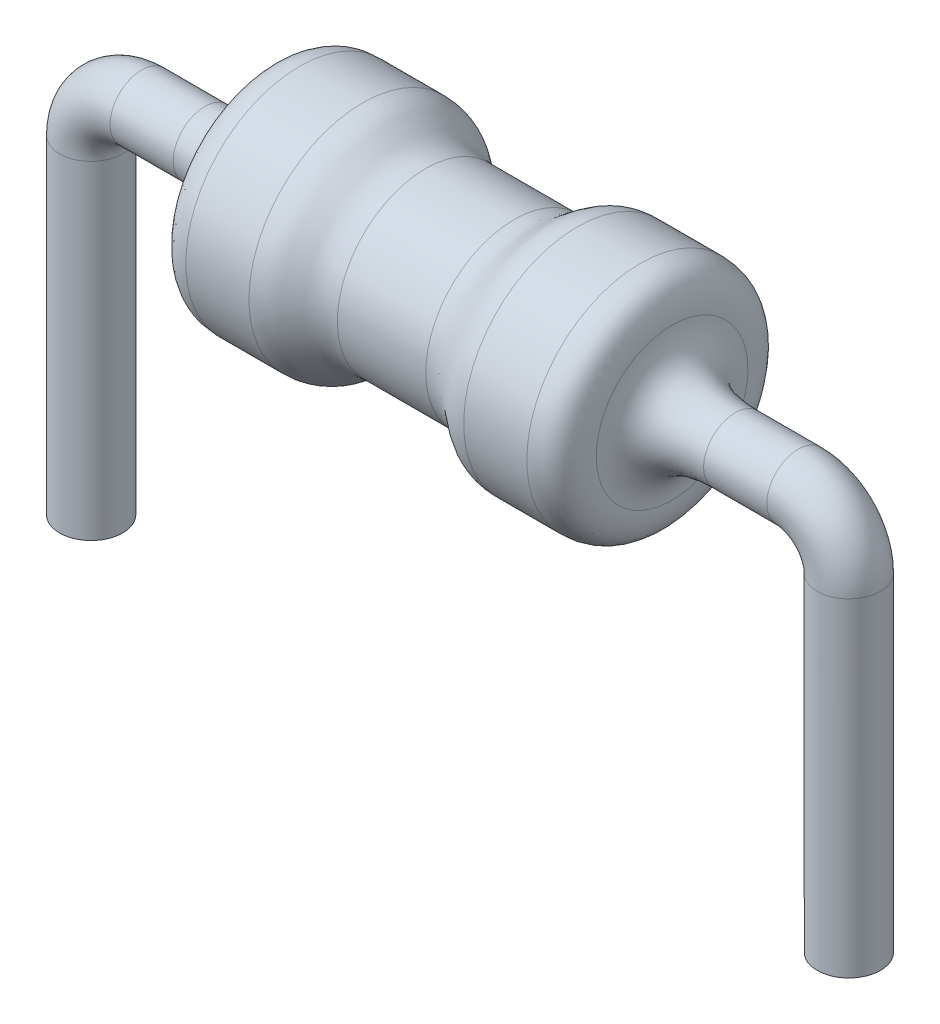
SolidWorks part; units mm, degrees
ref_plane "Front Plane" through (0, 0, 0) normal (0, 0, 1) x (1, 0, 0)
ref_plane "Top Plane" through (0, 0, 0) normal (0, 1, 0) x (1, 0, 0)
ref_plane "Right Plane" through (0, 0, 0) normal (1, 0, 0) x (0, 0, -1)
sketch "Эскиз1" plane through (0, 0, 0) normal (0, 0, 1) x (1, 0, 0)
  line L2 (-0.35, 0.7) -> (0.35, 0.7)
  line L3 (0.85, 0.9) -> (1.35, 0.9)
  line L4 (0, 0) -> (0, 0.7) construction
  line L5 (2.1, 0.25) -> (2.1, 0)
  line L7 (2.1, 0) -> (-2.1, 0)
  line L8 (-2.1, 0.25) -> (-2.1, 0)
  line L9 (-0.85, 0.9) -> (-1.35, 0.9)
  parabola Q2 (1.6, 0.6003) -> (1.35, 0.9) focus (1.4525, 0.7769) apex (1.513, 0.8495)
  parabola Q3 (2.1, 0.25) -> (1.6, 0.6003) focus (1.7644, 0.4851) apex (1.654, 0.4079)
  parabola Q4 (-2.1, 0.25) -> (-1.6, 0.6003) focus (-1.7644, 0.4851) apex (-1.654, 0.4079)
  parabola Q5 (-1.6, 0.6003) -> (-1.35, 0.9) focus (-1.4525, 0.7769) apex (-1.513, 0.8495)
  spline S1 degree 3 poles (0.85, 0.9) (0.6, 0.9) (0.6, 0.7) (0.35, 0.7) knots 0 0 0 0 1 1 1 1
  spline S2 degree 3 poles (-0.85, 0.9) (-0.6, 0.9) (-0.6, 0.7) (-0.35, 0.7) knots 0 0 0 0 1 1 1 1
revolve "Повернуть1" add sketch "Эскиз1" angle 360 about L7
sketch "Эскиз2" plane through (0, 0, 0) normal (0, 0, 1) x (1, 0, 0)
  line L0 (0, 0) -> (2.6, 0)
  line L1 (3, -0.4) -> (3, -3)
  arc A0 (3, -0.4) -> (2.6, 0) centre (2.6, -0.4) ccw
  dimension "D2" = 0.4
  dimension "D1" = 3
  dimension "D3" = 3
ref_plane "Плоскость1" through (0, -3, 0) normal (0, 1, 0) x (1, 0, 0)
sketch "Эскиз3" plane through (0, -3, 0) normal (0, 1, 0) x (1, 0, 0)
  circle A0 centre (3, 0) radius 0.25
  dimension "D1" = 0.5
sweep "По траектории1" add profiles "Эскиз3" path "Эскиз2"
mirror "Зеркальное отражение1" about plane through (0, 0, 0) normal (1, 0, 0) of "По траектории1"
